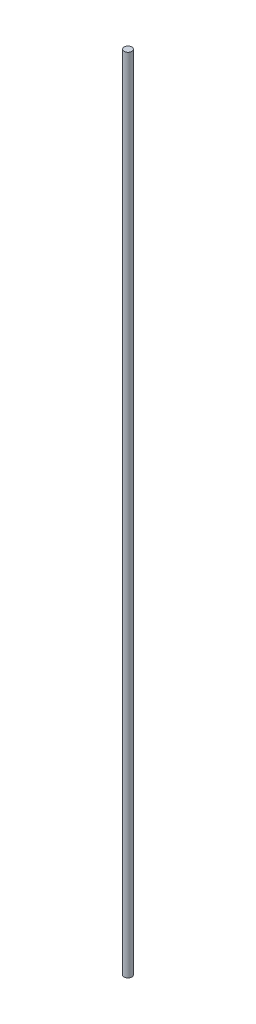
SolidWorks part; units mm, degrees
material "Kupfer"
ref_plane "Ebene vorne" through (0, 0, 0) normal (0, 0, 1) x (1, 0, 0)
ref_plane "Ebene oben" through (0, 0, 0) normal (0, 1, 0) x (1, 0, 0)
ref_plane "Ebene rechts" through (0, 0, 0) normal (1, 0, 0) x (0, 0, -1)
sketch "Skizze1" plane through (0, 0, 0) normal (0, 1, 0) x (1, 0, 0)
  circle A0 centre (0, 0) radius 0.75
  dimension "D1" = 1.5
extrude "Aufsatz-Linear austragen1" add sketch "Skizze1" along normal blind 155
